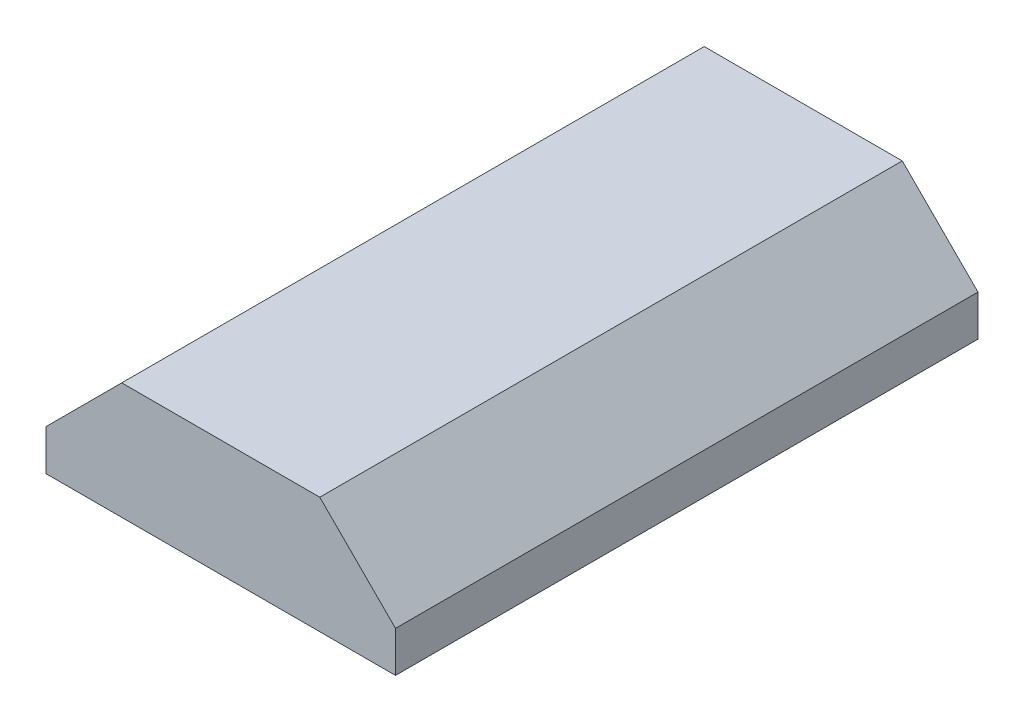
SolidWorks part; units mm, degrees
ref_plane "Ebene vorne" through (0, 0, 0) normal (0, 0, 1) x (1, 0, 0)
ref_plane "Ebene oben" through (0, 0, 0) normal (0, 1, 0) x (1, 0, 0)
ref_plane "Ebene rechts" through (0, 0, 0) normal (1, 0, 0) x (0, 0, -1)
sketch "Skizze1" plane through (0, 0, 0) normal (0, 0, 1) x (1, 0, 0)
  line L0 (0, 0) -> (0, 23680.6173) construction
  line L1 (3.4, 1.8089) -> (-3.4, 1.8089)
  line L2 (-3.4, 1.8089) -> (-6, -0.7911)
  line L3 (-6, -0.7911) -> (-6, -2.1911)
  line L4 (-6, -2.1911) -> (6, -2.1911)
  line L5 (6, -0.7911) -> (6, -2.1911)
  line L6 (3.4, 1.8089) -> (6, -0.7911)
  point P9 (0, -2.1911)
  point P11 (0, 1.8089)
  dimension "D1" = 3.4
  dimension "D2" = 6
  dimension "D3" = 4
  dimension "D4" = 135
extrude "Aufsatz-Linear austragen1" add sketch "Skizze1" along normal blind 20 contours L1 L2 L3 L4 L5 L6
